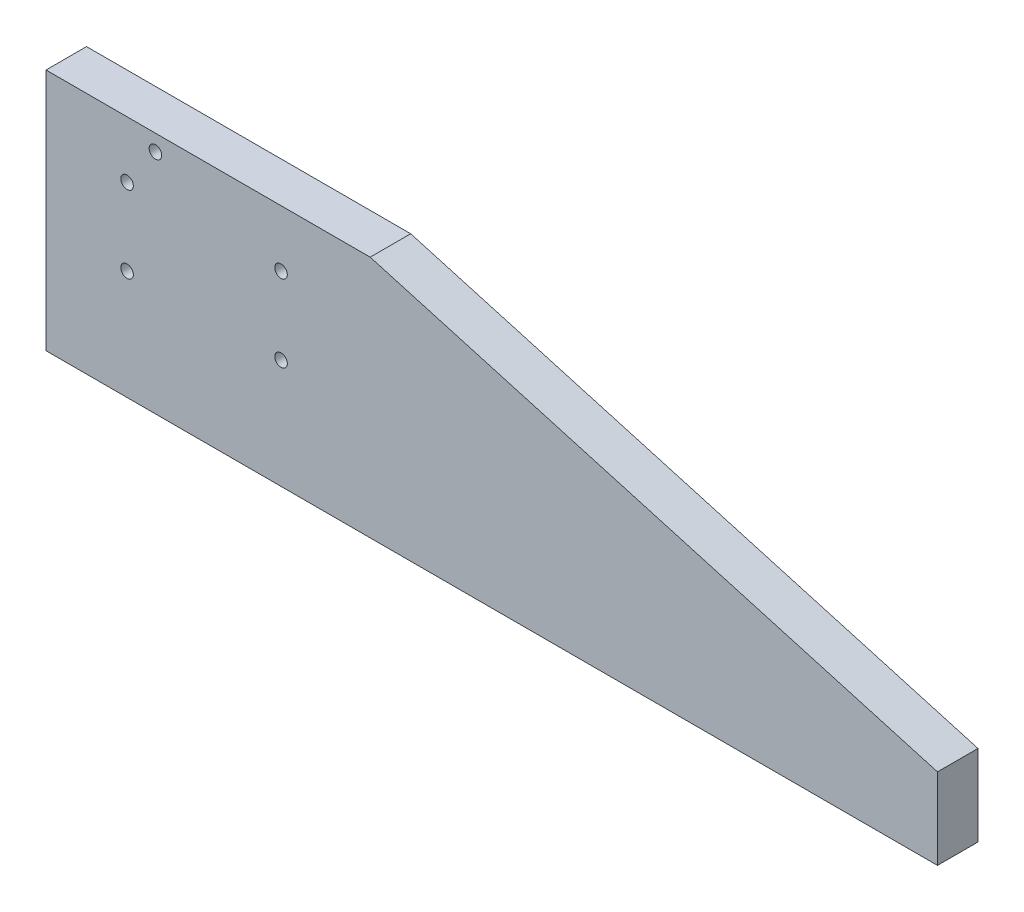
SolidWorks part; units mm, degrees
ref_plane "Front" through (0, 0, 0) normal (0, 0, 1) x (1, 0, 0)
ref_plane "Top" through (0, 0, 0) normal (0, 1, 0) x (1, 0, 0)
ref_plane "Right" through (0, 0, 0) normal (1, 0, 0) x (0, 0, -1)
sketch "Sketch1" plane through (0, 0, 0) normal (0, 0, 1) x (1, 0, 0)
  line L0 (110, -10) -> (-30, 30)
  line L1 (-110, -30) -> (110, -30)
  line L2 (-110, -30) -> (-110, 30)
  line L3 (-110, 30) -> (110, 30)
  line L4 (110, -30) -> (110, 30)
  line L5 (-110, -30) -> (110, 30) construction
  line L6 (-110, 30) -> (110, -30) construction
  point P0 (0, 0)
  dimension "D1" = 60
  dimension "D2" = 220
  dimension "D3" = 80
  dimension "D4" = 20
extrude "Boss-Extrude1" add sketch "Sketch1" along normal blind 10 contours L1 L4 L0 L3 L2
sketch "Sketch2" plane through (0, 0, 10) normal (0, 0, 1) x (1, 0, 0)
  line L0 (-110, -30) -> (-110, 30) construction
  line L1 (-90, 16) -> (-52, 16) construction
  line L2 (-90, 16) -> (-90, -3) construction
  line L3 (-90, -3) -> (-52, -3) construction
  line L4 (-52, 16) -> (-52, -3) construction
  line L5 (-90, 16) -> (-52, -3) construction
  line L6 (-90, -3) -> (-52, 16) construction
  line L7 (-110, 30) -> (-30, 30) construction
  circle A0 centre (-90, 16) radius 1.55
  circle A1 centre (-52, 16) radius 1.55
  circle A2 centre (-90, -3) radius 1.55
  circle A3 centre (-52, -3) radius 1.55
  point P0 (-71, 6.5)
  dimension "D3" = 3.1
  dimension "D4" = 3.1
  dimension "D5" = 3.1
  dimension "D6" = 3.1
  dimension "D1" = 19
  dimension "D2" = 38
  dimension "D7" = 20
  dimension "D8" = 14
extrude "Cut-Extrude1" cut sketch "Sketch2" against normal through all
sketch "Sketch3" plane through (0, 0, 10) normal (0, 0, 1) x (1, 0, 0)
  line L0 (-110, 30) -> (-30, 30) construction
  line L1 (-110, -30) -> (-110, 30) construction
  circle A0 centre (-83, 26) radius 1.55
  dimension "D1" = 3.1
  dimension "D2" = 4
  dimension "D3" = 27
extrude "Cut-Extrude2" cut sketch "Sketch3" against normal up to next
